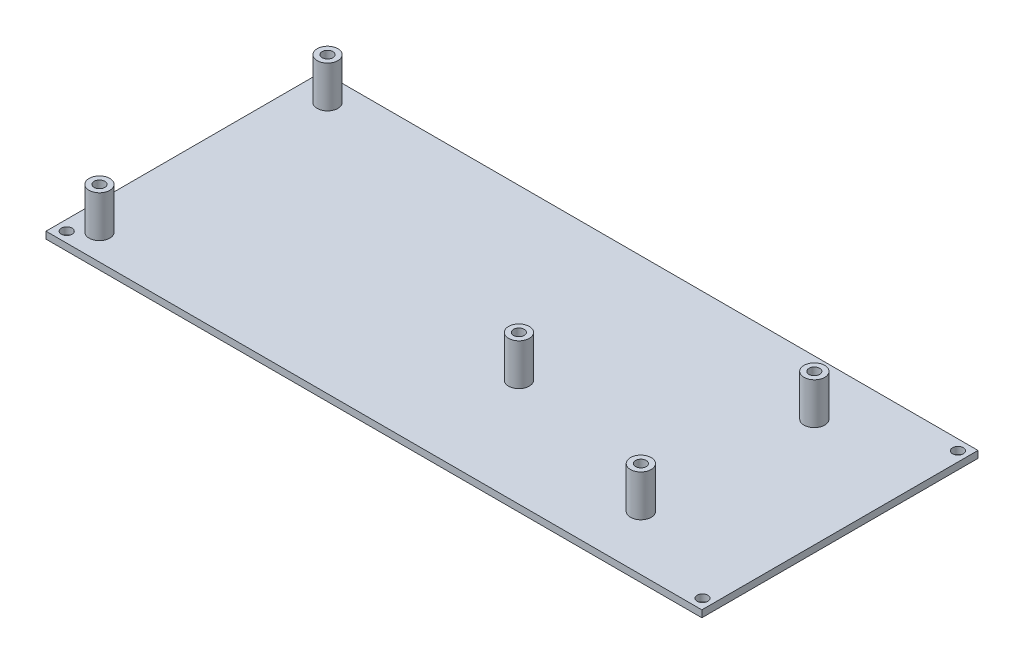
SolidWorks part; units mm, degrees
ref_plane "Front Plane" through (0, 0, 0) normal (0, 0, 1) x (1, 0, 0)
ref_plane "Top Plane" through (0, 0, 0) normal (0, 1, 0) x (1, 0, 0)
ref_plane "Right Plane" through (0, 0, 0) normal (1, 0, 0) x (0, 0, -1)
sketch "Sketch1" plane through (0, 0, 0) normal (0, 1, 0) x (1, 0, 0)
  line L1 (-75.7488, 40.5797) -> (114.2512, 40.5797)
  line L2 (-75.7488, 40.5797) -> (-75.7488, -39.4203)
  line L3 (-75.7488, -39.4203) -> (114.2512, -39.4203)
  line L4 (114.2512, 40.5797) -> (114.2512, -39.4203)
  circle A0 centre (-72.7488, 37.5797) radius 1.55
  circle A1 centre (111.4359, 37.5797) radius 1.55
  circle A2 centre (111.4359, -36.4203) radius 1.55
  circle A3 centre (-72.7488, -36.4203) radius 1.55
  point P12 (0, 0)
  point P13 (0, 0)
  point P14 (0, 0)
  point P15 (0, 0)
  point P16 (0, 0)
  point P17 (-73.3163, 38.3776)
  dimension "D3" = 3.1
  dimension "D1" = 80
  dimension "D2" = 190
  dimension "D4" = 3
  dimension "D5" = 3
  dimension "D6" = 3
extrude "Boss-Extrude1" add sketch "Sketch1" along normal blind 2
sketch "Sketch2" plane through (0, 2, 0) normal (0, 1, 0) x (1, 0, 0)
  line L0 (-75.7488, 40.5797) -> (-75.7488, -39.4203) construction
  line L1 (27.7512, 35.5797) -> (110.2512, 35.5797) construction
  line L2 (27.7512, 35.5797) -> (27.7512, -34.4203) construction
  line L3 (27.7512, -34.4203) -> (110.2512, -34.4203) construction
  line L4 (110.2512, 35.5797) -> (110.2512, -34.4203) construction
  line L5 (-71.7488, 37.2097) -> (20.0912, 37.2097) construction
  line L6 (-71.7488, 37.2097) -> (-71.7488, -36.0503) construction
  line L7 (-71.7488, -36.0503) -> (20.0912, -36.0503) construction
  line L8 (-98.3486, 0.5797) -> (132.2607, 0.5797) construction
  line L9 (114.2512, 40.5797) -> (-75.7488, 40.5797) construction
  line L10 (-75.7488, -39.4203) -> (114.2512, -39.4203) construction
  line L11 (114.2512, -39.4203) -> (114.2512, 40.5797) construction
  line L12 (20.0912, 37.2097) -> (20.0912, -36.0503) construction
  circle A0 centre (82.7112, 24.7097) radius 3
  circle A1 centre (80.7112, -23.5503) radius 3
  circle A2 centre (30.1412, -8.3103) radius 3
  circle A3 centre (82.7112, 24.7097) radius 1.55
  circle A4 centre (80.7112, -23.5503) radius 1.55
  circle A5 centre (30.1412, -8.3103) radius 1.55
  circle A6 centre (-67.2588, 33.6497) radius 3
  circle A7 centre (-67.7488, -31.9303) radius 3
  circle A8 centre (-67.2588, 33.6497) radius 1.55
  circle A9 centre (-67.7488, -31.9303) radius 1.55
  dimension "D4" = 6
  dimension "D11" = 3.1
  dimension "D1" = 70
  dimension "D2" = 82.5
  dimension "D3" = 4
  dimension "D5" = 27.54
  dimension "D6" = 10.87
  dimension "D7" = 29.54
  dimension "D8" = 10.87
  dimension "D9" = 2.39
  dimension "D10" = 33.02
  dimension "D12" = 73.26
  dimension "D13" = 91.84
  dimension "D14" = 4
  dimension "D15" = 3.56
  dimension "D16" = 4.49
  dimension "D17" = 4.12
  dimension "D18" = 4
extrude "Boss-Extrude2" add sketch "Sketch2" along normal blind 12
